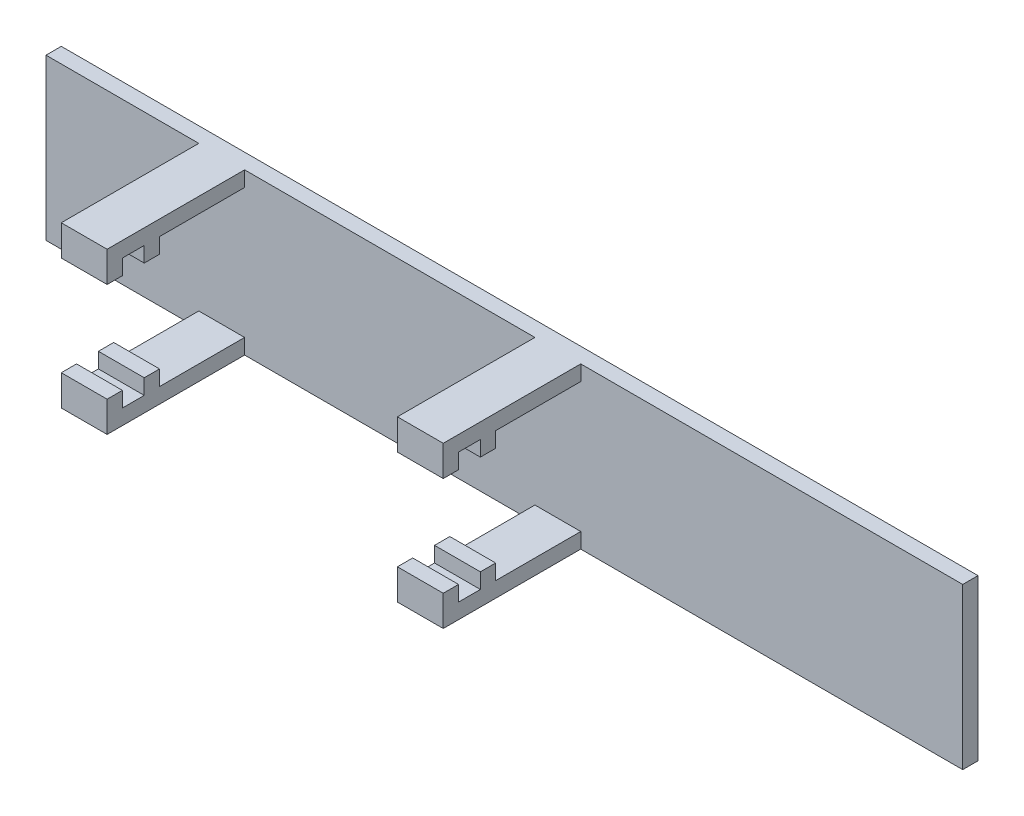
SolidWorks part; units mm, degrees
ref_plane "Front Plane" through (0, 0, 0) normal (0, 0, 1) x (1, 0, 0)
ref_plane "Top Plane" through (0, 0, 0) normal (0, 1, 0) x (1, 0, 0)
ref_plane "Right Plane" through (0, 0, 0) normal (1, 0, 0) x (0, 0, -1)
sketch "Sketch1" plane through (0, 0, 0) normal (0, 0, 1) x (1, 0, 0)
  line L1 (0, 0) -> (60, 0)
  line L2 (0, 0) -> (0, 10.5)
  line L3 (0, 10.5) -> (60, 10.5)
  line L4 (60, 0) -> (60, 10.5)
  dimension "D1" = 60
  dimension "D2" = 10.5
extrude "Boss-Extrude1" add sketch "Sketch1" along normal blind 1
sketch "Sketch2" plane through (0, 0, 0) normal (0, -1, 0) x (1, 0, 0)
  line L0 (0, 0) -> (60, 0) construction
  line L1 (10, 0) -> (13, 0)
  line L2 (10, 0) -> (10, 10)
  line L3 (10, 10) -> (13, 10)
  line L4 (13, 0) -> (13, 10)
  dimension "D1" = 10
  dimension "D2" = 3
  dimension "D3" = 10
extrude "Boss-Extrude2" add sketch "Sketch2" against normal blind 1
sketch "Sketch3" plane through (0, 1, 0) normal (0, 1, 0) x (1, 0, 0)
  line L0 (13, -1) -> (13, -10) construction
  line L1 (10, -10) -> (13, -10)
  line L2 (10, -10) -> (10, -6.57)
  line L3 (10, -6.57) -> (13, -6.57)
  line L4 (13, -10) -> (13, -6.57)
  dimension "D1" = 3.43
extrude "Boss-Extrude3" add sketch "Sketch3" along normal blind 1
sketch "Sketch4" plane through (0, 2, 0) normal (0, 1, 0) x (1, 0, 0)
  line L0 (10, -6.57) -> (10, -10) construction
  line L1 (10, -7.57) -> (13, -7.57)
  line L2 (10, -7.57) -> (10, -9)
  line L3 (10, -9) -> (13, -9)
  line L4 (13, -7.57) -> (13, -9)
  line L5 (13, -10) -> (13, -6.57) construction
  dimension "D1" = 1.43
  dimension "D2" = 1
extrude "Cut-Extrude1" cut sketch "Sketch4" against normal blind 1
sketch "Sketch6" plane through (0, 10.5, 0) normal (0, 1, 0) x (1, 0, 0)
  line L0 (60, 0) -> (0, 0) construction
  line L1 (10, 0) -> (13, 0)
  line L2 (10, 0) -> (10, -10)
  line L3 (10, -10) -> (13, -10)
  line L4 (13, 0) -> (13, -10)
  dimension "D1" = 3
extrude "Boss-Extrude4" add sketch "Sketch6" against normal blind 1
sketch "Sketch7" plane through (0, 9.5, 0) normal (0, -1, 0) x (1, 0, 0)
  line L0 (13, 10) -> (13, 1) construction
  line L1 (10, 10) -> (13, 10)
  line L2 (10, 10) -> (10, 6.57)
  line L3 (10, 6.57) -> (13, 6.57)
  line L4 (13, 10) -> (13, 6.57)
  dimension "D1" = 3.43
extrude "Boss-Extrude5" add sketch "Sketch7" along normal blind 1
sketch "Sketch8" plane through (0, 8.5, 0) normal (0, -1, 0) x (1, 0, 0)
  line L0 (10, 10) -> (10, 6.57) construction
  line L1 (10, 9) -> (13, 9)
  line L2 (10, 9) -> (10, 7.57)
  line L3 (10, 7.57) -> (13, 7.57)
  line L4 (13, 9) -> (13, 7.57)
  line L5 (13, 6.57) -> (13, 10) construction
  dimension "D1" = 1.43
  dimension "D2" = 1
extrude "Cut-Extrude2" cut sketch "Sketch8" against normal blind 1
sketch "Sketch9" plane through (0, 0, 0) normal (0, -1, 0) x (1, 0, 0)
  line L0 (0, 0) -> (60, 0) construction
  line L1 (35, 0) -> (32, 0)
  line L2 (35, 0) -> (35, 10)
  line L3 (35, 10) -> (32, 10)
  line L4 (32, 0) -> (32, 10)
  dimension "D1" = 10
  dimension "D2" = 3
  dimension "D3" = 25
extrude "Boss-Extrude6" add sketch "Sketch9" against normal blind 1
sketch "Sketch10" plane through (0, 1, 0) normal (0, 1, 0) x (1, 0, 0)
  line L0 (32, -10) -> (32, -1) construction
  line L1 (35, -10) -> (32, -10)
  line L2 (35, -10) -> (35, -6.57)
  line L3 (35, -6.57) -> (32, -6.57)
  line L4 (32, -10) -> (32, -6.57)
  dimension "D1" = 3.43
extrude "Boss-Extrude7" add sketch "Sketch10" along normal blind 1
sketch "Sketch11" plane through (0, 2, 0) normal (0, 1, 0) x (1, 0, 0)
  line L0 (32, -6.57) -> (32, -10) construction
  line L1 (32, -7.57) -> (35, -7.57)
  line L2 (32, -7.57) -> (32, -9)
  line L3 (32, -9) -> (35, -9)
  line L4 (35, -7.57) -> (35, -9)
  line L5 (35, -10) -> (35, -6.57) construction
  dimension "D1" = 1.43
  dimension "D2" = 1
extrude "Cut-Extrude3" cut sketch "Sketch11" against normal blind 1
sketch "Sketch12" plane through (0, 10.5, 0) normal (0, 1, 0) x (1, 0, 0)
  line L0 (60, 0) -> (0, 0) construction
  line L1 (32, 0) -> (35, 0)
  line L2 (32, 0) -> (32, -10)
  line L3 (32, -10) -> (35, -10)
  line L4 (35, 0) -> (35, -10)
  dimension "D1" = 3
extrude "Boss-Extrude8" add sketch "Sketch12" against normal blind 1
sketch "Sketch13" plane through (0, 9.5, 0) normal (0, -1, 0) x (1, 0, 0)
  line L0 (35, 10) -> (35, 1) construction
  line L1 (32, 10) -> (35, 10)
  line L2 (32, 10) -> (32, 6.57)
  line L3 (32, 6.57) -> (35, 6.57)
  line L4 (35, 10) -> (35, 6.57)
  dimension "D1" = 3.43
extrude "Boss-Extrude9" add sketch "Sketch13" along normal blind 1
sketch "Sketch14" plane through (0, 8.5, 0) normal (0, -1, 0) x (1, 0, 0)
  line L0 (32, 10) -> (32, 6.57) construction
  line L1 (32, 9) -> (35, 9)
  line L2 (32, 9) -> (32, 7.57)
  line L3 (32, 7.57) -> (35, 7.57)
  line L4 (35, 9) -> (35, 7.57)
  line L5 (35, 6.57) -> (35, 10) construction
  dimension "D1" = 1.43
  dimension "D2" = 1
extrude "Cut-Extrude4" cut sketch "Sketch14" against normal blind 1
